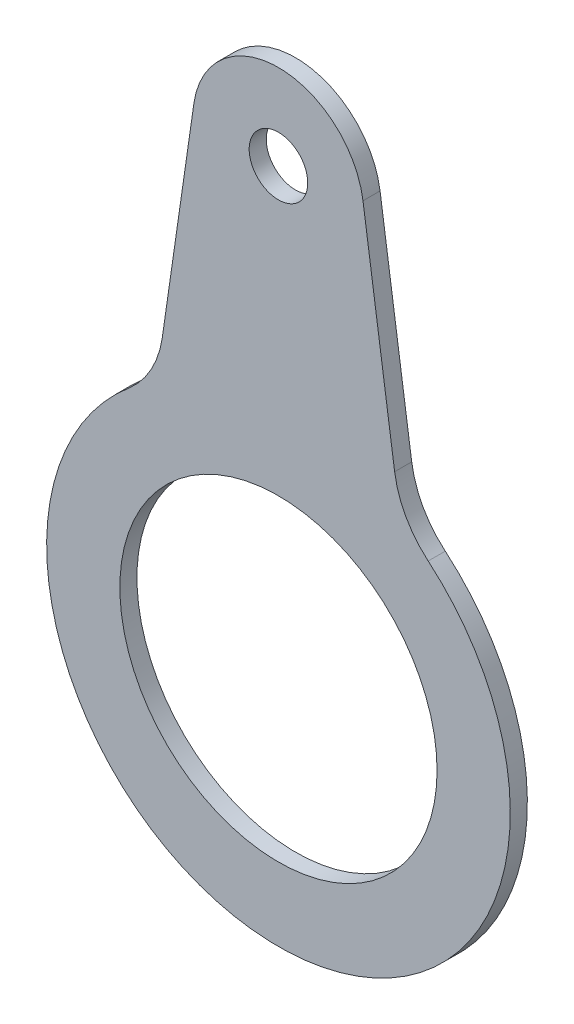
SolidWorks part; units mm, degrees
ref_plane "Спереди" through (0, 0, 0) normal (0, 0, 1) x (1, 0, 0)
ref_plane "Сверху" through (0, 0, 0) normal (0, 1, 0) x (1, 0, 0)
ref_plane "Справа" through (0, 0, 0) normal (1, 0, 0) x (0, 0, -1)
sketch "Эскиз1" plane through (0, 0, 0) normal (0, 0, 1) x (1, 0, 0)
  line L0 (0, 0) -> (0, 9.1003) construction
  line L2 (2.3803, 4.867) -> (1.732, 9.3507)
  line L3 (-2.3803, 4.867) -> (-1.732, 9.3507)
  circle A0 centre (0, 0) radius 3.25
  arc A1 (-3.0679, 3.6263) -> (3.0679, 3.6263) centre (0, 0) ccw
  circle A2 centre (0, 9.1003) radius 0.6
  arc A3 (1.732, 9.3507) -> (-1.732, 9.3507) centre (0, 9.1003) ccw
  arc A4 (-3.0679, 3.6263) -> (-2.3803, 4.867) centre (-4.3597, 5.1532) ccw
  arc A5 (3.0679, 3.6263) -> (2.3803, 4.867) centre (4.3597, 5.1532) cw
  point P11 (-2.5, 4.0389)
  point P14 (2.5, 4.0389)
  dimension "D1" = 6.5
  dimension "D2" = 9.5
  dimension "D3" = 3.5
  dimension "D4" = 1.2
  dimension "D6" = 2
  dimension "D5" = 5
extrude "Вытянуть1" add sketch "Эскиз1" along normal blind 0.35
